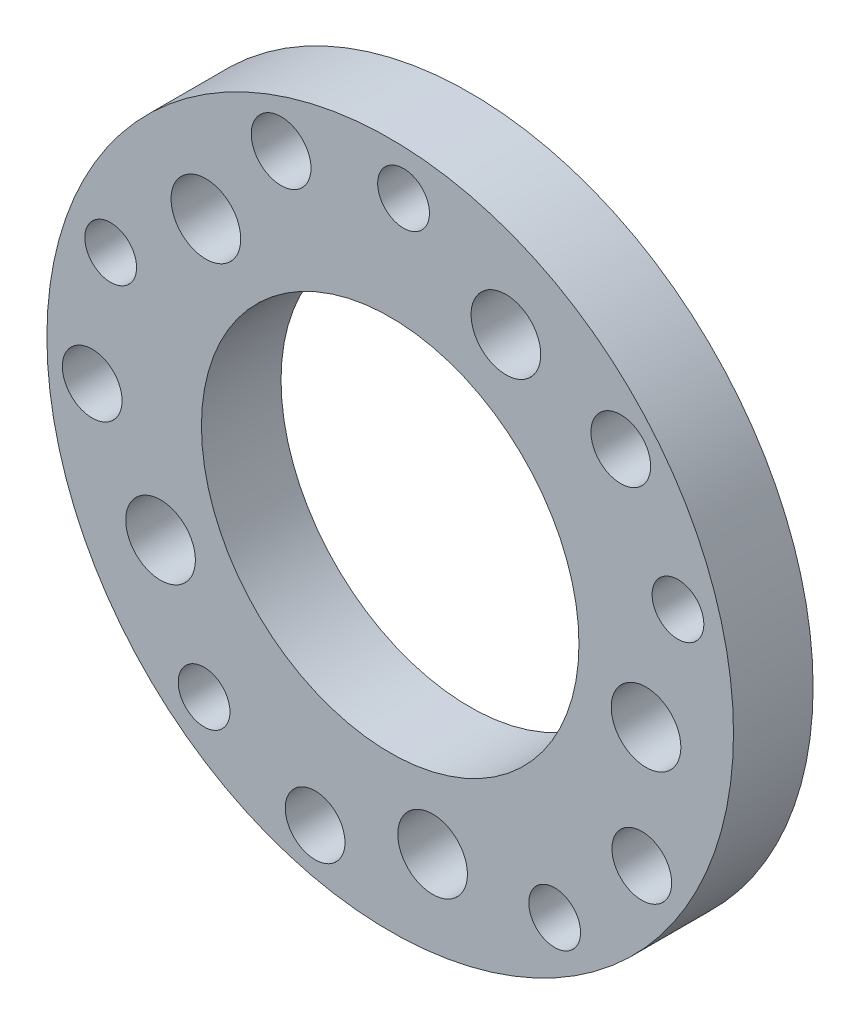
SolidWorks part; units mm, degrees
ref_plane "前视基准面" through (0, 0, 0) normal (0, 0, 1) x (1, 0, 0)
ref_plane "上视基准面" through (0, 0, 0) normal (0, 1, 0) x (1, 0, 0)
ref_plane "右视基准面" through (0, 0, 0) normal (1, 0, 0) x (0, 0, -1)
sketch "草图1" plane through (0, 0, 0) normal (0, 0, 1) x (1, 0, 0)
  line L0 (0.6719, 14.9849) -> (14.4592, 3.9916) construction
  line L1 (0.6719, 14.9849) -> (0, 0) construction
  line L2 (5.9133, 7.4161) -> (10.7543, 13.4873) construction
  line L3 (0, 0) -> (14.4592, 3.9916) construction
  line L4 (0, 0) -> (18.6038, 15.299) construction
  line L5 (0, 0) -> (10.0467, 20.0912) construction
  circle A0 centre (0, 0) radius 9.485
  circle A1 centre (0, 0) radius 17.25
  circle A2 centre (8.2643, -12.518) radius 1.3
  circle A3 centre (0, 0) radius 15 construction
  circle A9 centre (-9.3515, -11.7281) radius 1.3
  circle A11 centre (-14.0439, 5.2696) radius 1.3
  circle A13 centre (0.6719, 14.9849) radius 1.3
  circle A15 centre (14.4592, 3.9916) radius 1.3
  circle A17 centre (-0.6719, -14.9849) radius 1.3 [skipped]
  circle A18 centre (-14.4592, -3.9916) radius 1.3 [skipped]
  circle A19 centre (-8.2643, 12.518) radius 1.3 [skipped]
  circle A20 centre (9.3515, 11.7281) radius 1.3 [skipped]
  circle A21 centre (14.0439, -5.2696) radius 1.3 [skipped]
  circle A29 centre (11.5856, 9.5275) radius 1.5
  circle A30 centre (12.6414, -8.0744) radius 1.5
  circle A31 centre (-3.7728, -14.5178) radius 1.5
  circle A32 centre (-14.9731, -0.8981) radius 1.5
  circle A33 centre (-5.4811, 13.9627) radius 1.5
  circle A34 centre (0, 0) radius 13 construction
  circle A35 centre (5.8143, 11.6273) radius 1.75
  circle A36 centre (12.8549, -1.9367) radius 1.75
  circle A37 centre (2.1305, -12.8242) radius 1.75
  circle A38 centre (-11.5382, -5.9892) radius 1.75
  circle A39 centre (-9.2615, 9.1227) radius 1.75
  dimension "D1" = 18.97
  dimension "D2" = 2.6
  dimension "D3" = 30
  dimension "D4" = 34.5
  dimension "D6" = 72
  dimension "D7" = 24
  dimension "D8" = 5
  dimension "D9" = 24
  dimension "D10" = 5
  dimension "D5" = 10
extrude "凸台-拉伸1" add sketch "草图1" along normal blind 4
